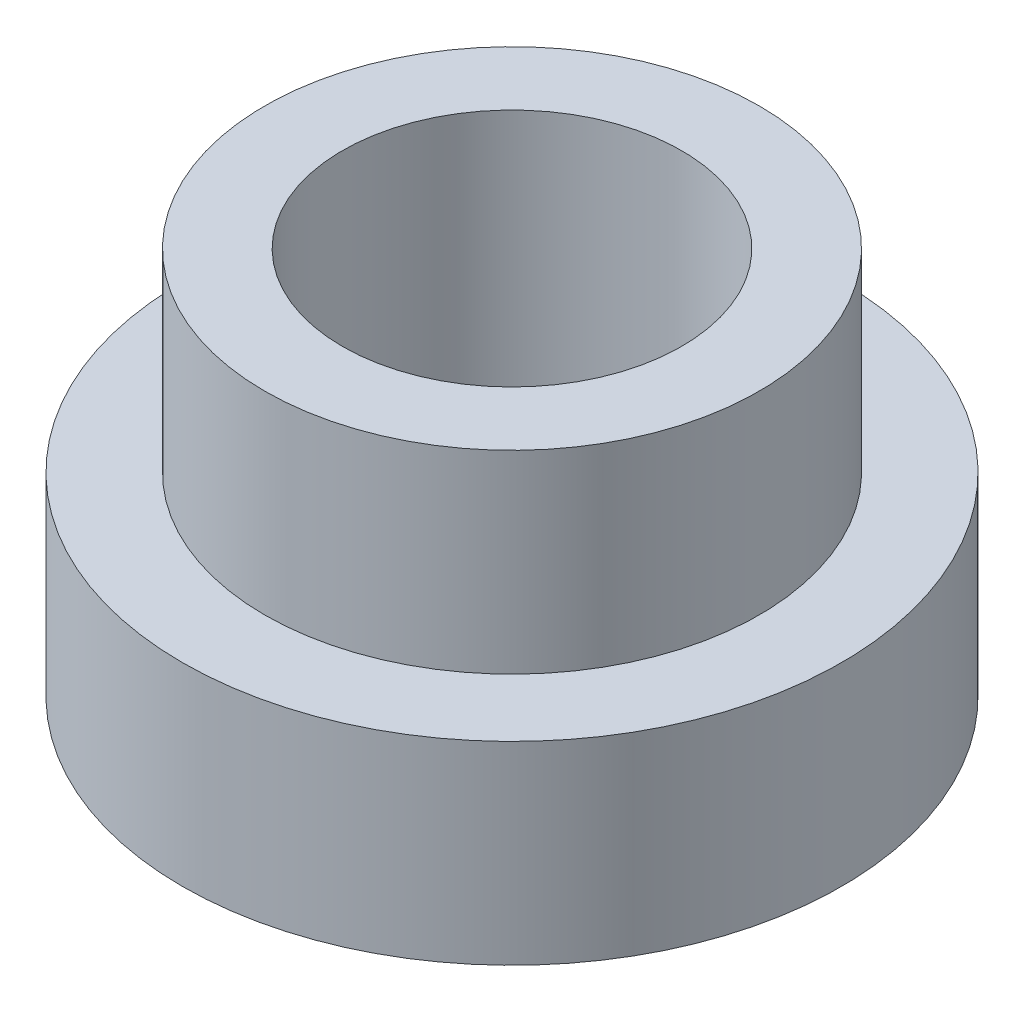
SolidWorks part; units mm, degrees
ref_plane "Přední rovina" through (0, 0, 0) normal (0, 0, 1) x (1, 0, 0)
ref_plane "Horní rovina" through (0, 0, 0) normal (0, 1, 0) x (1, 0, 0)
ref_plane "Pravá rovina" through (0, 0, 0) normal (1, 0, 0) x (0, 0, -1)
sketch "Skica1" plane through (0, 0, 0) normal (0, 0, 1) x (1, 0, 0)
  line L0 (0, 0) -> (-3.4, 0)
  line L1 (-3.4, 0) -> (-3.4, 2)
  line L2 (-3.4, 2) -> (-2.55, 2)
  line L3 (-2.55, 2) -> (-2.55, 4)
  line L4 (-2.55, 4) -> (0, 4)
  line L5 (0, 4) -> (0, 0) construction
  line L6 (-1.75, 4) -> (-1.75, 0)
  dimension "D1" = 3.5
  dimension "D2" = 5.1
  dimension "D3" = 6.8
  dimension "D4" = 2
  dimension "D5" = 2
  dimension "D6" = 0.8
revolve "Rotovat1" add sketch "Skica1" angle 360 about L5
sketch "Skica2" [suppressed] plane through (0, 0, 0) normal (0, 1, 0) x (1, 0, 0)
  line L1 (0, 0) -> (-10, 0)
  line L2 (0, 0) -> (0, 10)
  line L3 (0, 10) -> (-10, 10)
  line L4 (-10, 0) -> (-10, 10)
  dimension "D1" = 10
  dimension "D2" = 10
pattern_linear "LinPole1" [suppressed] count 2 spacing 10 along (-1, 0, 0) count 2 spacing 10 along (0, 0, -1)
sketch "Skica3" [suppressed] plane through (0, 0, 0) normal (0, -1, 0) x (1, 0, 0)
  line L0 (-10, 0) -> (-10, -10) construction
  line L1 (-6.9077, 1) -> (-3.0923, 1)
  line L2 (-6.9077, 1) -> (-6.9077, -1)
  line L3 (-6.9077, -1) -> (-3.0923, -1)
  line L4 (-3.0923, 1) -> (-3.0923, -1)
  line L5 (-1, -3.0923) -> (1, -3.0923)
  line L6 (-1, -3.0923) -> (-1, -6.9077)
  line L7 (-1, -6.9077) -> (1, -6.9077)
  line L8 (1, -3.0923) -> (1, -6.9077)
  line L9 (-3.0923, -11) -> (-6.9077, -11)
  line L10 (-3.0923, -11) -> (-3.0923, -9)
  line L11 (-3.0923, -9) -> (-6.9077, -9)
  line L12 (-6.9077, -11) -> (-6.9077, -9)
  line L13 (-9, -6.9077) -> (-11, -6.9077)
  line L14 (-9, -6.9077) -> (-9, -3.0923)
  line L15 (-9, -3.0923) -> (-11, -3.0923)
  line L16 (-11, -6.9077) -> (-11, -3.0923)
  line L17 (0, -10) -> (-10, -10) construction
  line L18 (0, 0) -> (0, -10) construction
  line L19 (0, 0) -> (-10, 0) construction
  circle A0 centre (-10, 0) radius 3.25 construction
  circle A1 centre (0, 0) radius 3.25 construction
  circle A2 centre (0, -10) radius 3.25 construction
  circle A3 centre (-10, -10) radius 3.25 construction
  point P24 (-10, -3.0923)
  point P27 (-6.9077, -10)
  point P30 (0, -6.9077)
  point P33 (-6.9077, 0)
  circle M17 centre (-10, 0) radius 3.25
  dimension "D1" = 2
extrude "Přidat vysunutím1" [suppressed] add sketch "Skica3" against normal blind 0.2 contours L4 L1 L3 M17 | L8 L5 L6 L7 | L12 L9 L10 L11 | L16 L15 L14 L13
